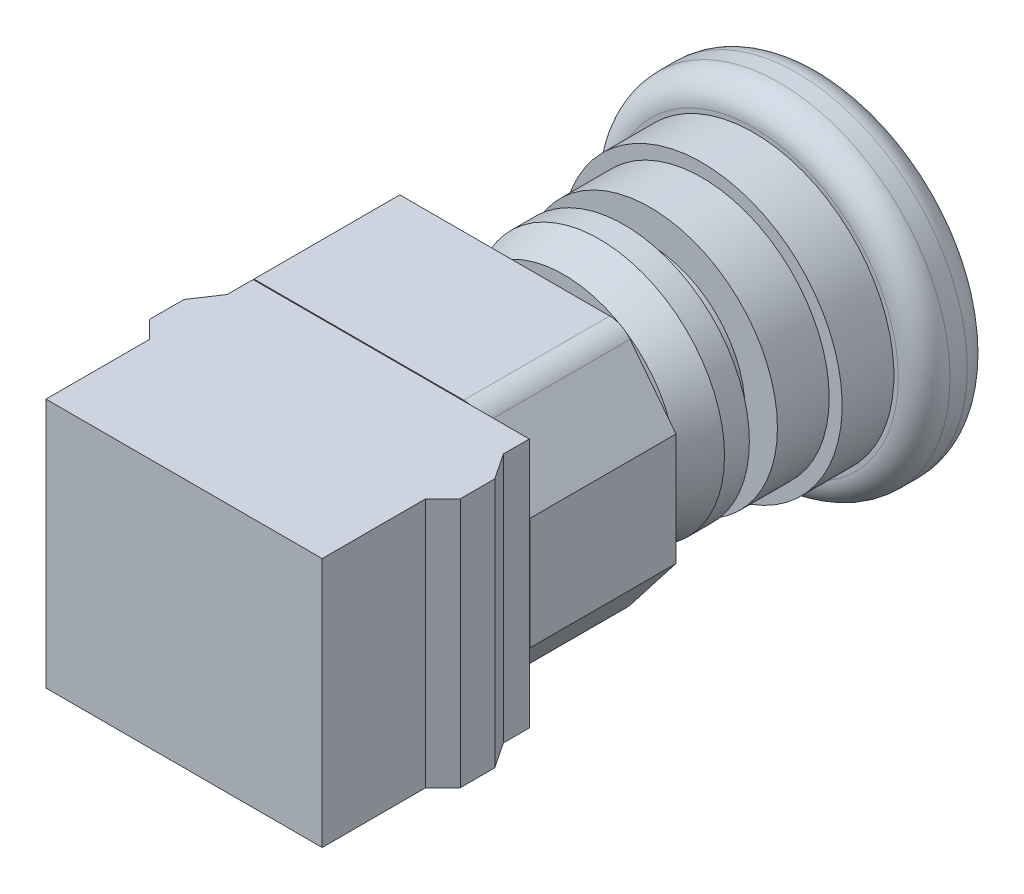
SolidWorks part; units mm, degrees
ref_plane "前视基准面" through (0, 0, 0) normal (0, 0, 1) x (1, 0, 0)
ref_plane "上视基准面" through (0, 0, 0) normal (0, 1, 0) x (1, 0, 0)
ref_plane "右视基准面" through (0, 0, 0) normal (1, 0, 0) x (0, 0, -1)
sketch "草图1" plane through (0, 0, 0) normal (0, 0, 1) x (1, 0, 0)
  line L1 (0, 0) -> (32, 0)
  line L2 (0, 0) -> (0, -29)
  line L3 (0, -29) -> (32, -29)
  line L4 (32, 0) -> (32, -29)
  dimension "D1" = 32
  dimension "D2" = 29
extrude "凸台-拉伸1" add sketch "草图1" along normal blind 12
sketch "草图2" plane through (0, 0, 0) normal (0, 1, 0) x (1, 0, 0)
  line L0 (0, 0) -> (-2, 2)
  line L1 (-2, 2) -> (-2, 6)
  line L2 (-2, 6) -> (0, 9)
  line L3 (0, 9) -> (0, 12)
  line L4 (0, -12) -> (0, 0) construction
  line L5 (32, 0) -> (0, 0) construction
  line L6 (32, 0) -> (0, 0)
  line L7 (32, 9) -> (32, 12)
  line L8 (34, 6) -> (32, 9)
  line L9 (34, 2) -> (34, 6)
  line L10 (32, 0) -> (34, 2)
  line L11 (0, 12) -> (29.3, 12)
  line L12 (16, 0) -> (16, 13.8485) construction
  line L13 (29.3, 12) -> (32, 12)
  dimension "D1" = 2
  dimension "D2" = 2
  dimension "D3" = 4
  dimension "D4" = 9
  dimension "D5" = 0
  dimension "D6" = 12
extrude "凸台-拉伸2" add sketch "草图2" against normal up to surface (29 mm away) up to face at (16, -29, 6)
sketch "草图3" plane through (0, 0, -12) normal (0, 0, -1) x (-1, 0, 0)
  line L0 (-25, 1) -> (0, 1)
  line L1 (-25, -30) -> (0, -30)
  line L2 (0, -29) -> (0, -30)
  line L3 (0, 0) -> (0, 1)
  line L4 (-25, -30) -> (-32, -21)
  line L5 (-32, -21) -> (-32, -8)
  line L6 (-32, -8) -> (-25, 1)
  line L7 (0, -29) -> (-32, -29) construction
  line L8 (-32, 0) -> (0, 0) construction
  line L9 (0, -29) -> (0, 0) construction
  circle A0 centre (-16, -14.5) radius 11
  line M1 (-32, -29) -> (0, -29)
  line M2 (0, -29) -> (0, 0)
  line M3 (0, 0) -> (-32, 0)
  line M5 (-32, 0) -> (-32, -29)
  dimension "D8" = 22
  dimension "D1" = 25
  dimension "D2" = 1
  dimension "D3" = 1
  dimension "D4" = 25
  dimension "D5" = 32
  dimension "D6" = 9
  dimension "D7" = 9
extrude "凸台-拉伸3" add sketch "草图3" along normal blind 17 contours L6 L4 A0 M5 M1 M2 M3
sketch "草图4" plane through (0, 0, -29) normal (0, 0, -1) x (-1, 0, 0)
  circle A0 centre (-16, -14.5) radius 11 construction
  circle A1 centre (-16, -14.5) radius 11
extrude "凸台-拉伸4" add sketch "草图4" along normal blind 3 separate body
sketch "草图5" plane through (0, 0, -32) normal (0, 0, -1) x (-1, 0, 0)
  circle A0 centre (-16, -14.5) radius 14.5
  dimension "D1" = 29
extrude "凸台-拉伸6" add sketch "草图5" along normal blind 10
sketch "草图6" plane through (0, 0, -42) normal (0, 0, -1) x (-1, 0, 0)
  circle A0 centre (-16, -14.5) radius 14.75
  dimension "D1" = 29.5
extrude "凸台-拉伸7" add sketch "草图6" along normal blind 6
sketch "草图7" plane through (0, 0, -48) normal (0, 0, -1) x (-1, 0, 0)
  circle A0 centre (-16, -14.5) radius 16.25
  dimension "D1" = 32.5
extrude "凸台-拉伸8" add sketch "草图7" along normal blind 6
sketch "草图8" plane through (0, 0, -54) normal (0, 0, -1) x (-1, 0, 0)
  circle A0 centre (-16, -14.5) radius 19.75
  dimension "D1" = 39.5
extrude "凸台-拉伸9" add sketch "草图8" along normal blind 8
sketch "草图9" plane through (0, 0, -42) normal (0, 0, 1) x (1, 0, 0)
  circle A0 centre (16, -14.5) radius 11
  circle A1 centre (16, -14.5) radius 22.5538
  dimension "D1" = 22
extrude "切除-拉伸1" cut sketch "草图9" along normal blind 3
chamfer "倒角1" distance 1.5 angle 70 1 edges at (1.5, -14.5, -32)
fillet "圆角1" radius 3 2 edges at (-3.75, -14.5, -54) (-3.75, -14.5, -62)
fillet "圆角2" radius 3 3 edges
sketch "草图10" plane through (0, 0, -12) normal (0, 0, -1) x (-1, 0, 0)
  line L0 (-32, -8) -> (-32, -21)
  line L1 (-24.3105, -29) -> (0, -29)
  line L2 (0, -29) -> (0, 0)
  line L3 (0, 0) -> (-24.3105, 0)
  line L4 (-32, -8) -> (-26.6786, -1.1582) construction
  line L5 (-26.6786, -27.8418) -> (-32, -21) construction
  line L6 (-26.6786, -27.8418) -> (-32, -21)
  line L7 (-32, -8) -> (-26.6786, -1.1582)
  line L8 (-31.9, -8.0343) -> (-31.9, -20.9657)
  line L9 (-26.5996, -27.7804) -> (-31.9, -20.9657)
  line L10 (-24.3105, -28.9) -> (-0.1, -28.9)
  line L11 (-0.1, -28.9) -> (-0.1, -0.1)
  line L12 (-0.1, -0.1) -> (-24.3105, -0.1)
  line L13 (-31.9, -8.0343) -> (-26.5996, -1.2196)
  arc A0 (-24.3105, 0) -> (-26.6786, -1.1582) centre (-24.3105, -3) ccw construction
  arc A1 (-26.6786, -27.8418) -> (-24.3105, -29) centre (-24.3105, -26) ccw construction
  arc A2 (-26.6786, -27.8418) -> (-24.3105, -29) centre (-24.3105, -26) ccw
  arc A3 (-24.3105, 0) -> (-26.6786, -1.1582) centre (-24.3105, -3) ccw
  arc A4 (-26.5996, -27.7804) -> (-24.3105, -28.9) centre (-24.3105, -26) ccw
  arc A5 (-24.3105, -0.1) -> (-26.5996, -1.2196) centre (-24.3105, -3) ccw
  dimension "D1" = 0.1
extrude "切除-拉伸2" cut sketch "草图10" along normal blind 0.1
